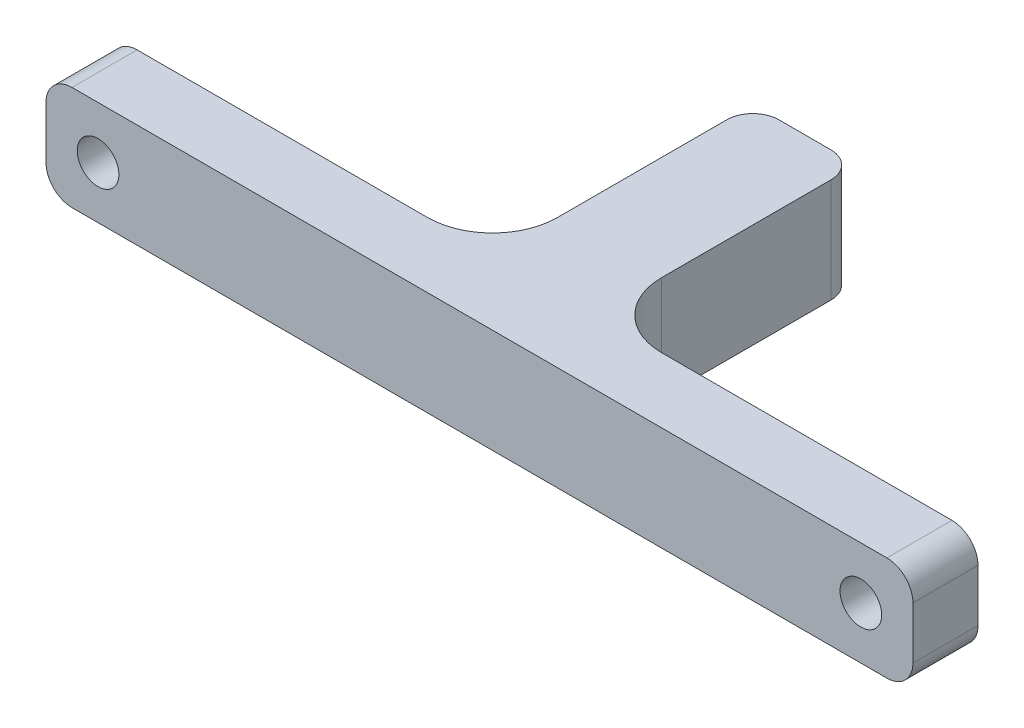
SolidWorks part; units mm, degrees
material "6061 合金"
ref_plane "前视基准面" through (0, 0, 0) normal (0, 0, 1) x (1, 0, 0)
ref_plane "上视基准面" through (0, 0, 0) normal (0, 1, 0) x (1, 0, 0)
ref_plane "右视基准面" through (0, 0, 0) normal (1, 0, 0) x (0, 0, -1)
sketch "草图1" plane through (0, 0, 0) normal (0, 0, 1) x (1, 0, 0)
  line L0 (0, 0) -> (-33.3, 0) construction
  line L1 (33.3, -4) -> (-33.3, -4)
  line L2 (33.3, -4) -> (33.3, 4)
  line L3 (33.3, 4) -> (-33.3, 4)
  line L4 (-33.3, -4) -> (-33.3, 4)
  line L5 (33.3, -4) -> (-33.3, 4) construction
  line L6 (33.3, 4) -> (-33.3, -4) construction
  line L7 (0, 0) -> (0, 3.551) construction
  circle A0 centre (-29.3, 0) radius 1.6
  circle A1 centre (29.3, 0) radius 1.6
  point P0 (0, 0)
  dimension "D3" = 3.2
  dimension "D1" = 66.6
  dimension "D2" = 8
  dimension "D4" = 4
extrude "凸台-拉伸1" add sketch "草图1" along normal blind 5
sketch "草图2" plane through (0, 4, 0) normal (0, 1, 0) x (1, 0, 0)
  line L0 (-4, 0) -> (-4, 20)
  line L1 (33.3, 0) -> (-33.3, 0) construction
  line L2 (-4, 20) -> (4, 20)
  line L3 (4, 20) -> (4, 0)
  line L4 (0, 0) -> (0, 38.0845) construction
  line L5 (33.3, -5) -> (-33.3, -5) construction
  line L6 (-4, 0) -> (4, 0)
  dimension "D1" = 4
  dimension "D2" = 4
  dimension "D3" = 25
extrude "凸台-拉伸2" add sketch "草图2" against normal blind 8
fillet "圆角1" radius 2 4 edges at (33.3, -4, 2.5) (33.3, 4, 2.5) (-33.3, -4, 2.5) (-33.3, 4, 2.5)
fillet "圆角2" radius 5 2 edges at (4, 0, 0) (-4, 0, 0)
fillet "圆角3" radius 2 2 edges at (4, 0, -20) (-4, 0, -20)
